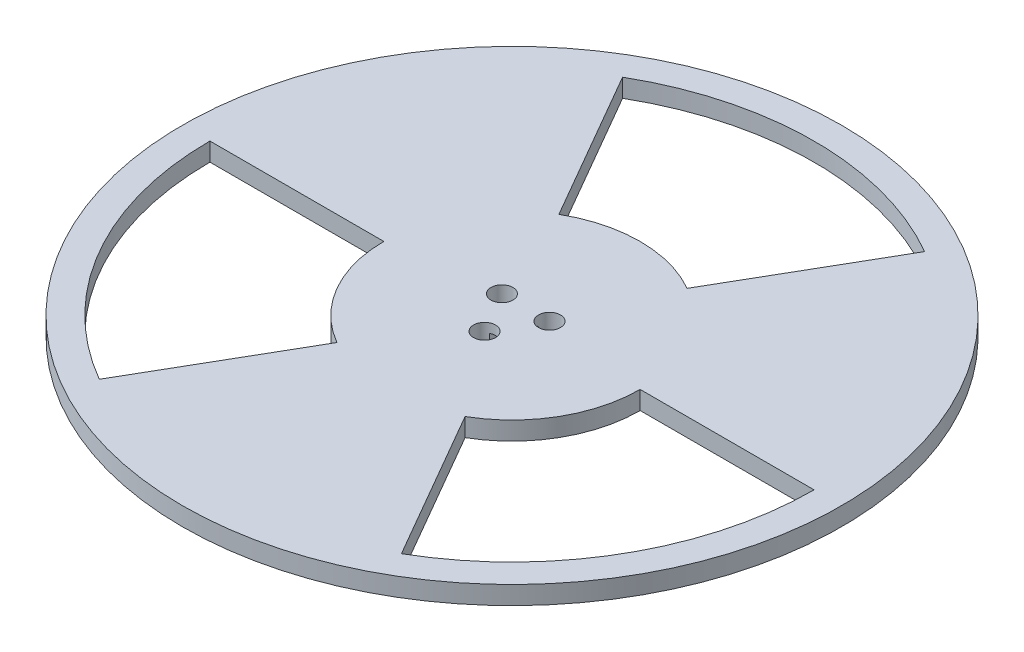
SolidWorks part; units mm, degrees
ref_plane "Front Plane" through (0, 0, 0) normal (0, 0, 1) x (1, 0, 0)
ref_plane "Top Plane" through (0, 0, 0) normal (0, 1, 0) x (1, 0, 0)
ref_plane "Right Plane" through (0, 0, 0) normal (1, 0, 0) x (0, 0, -1)
sketch "Sketch1" plane through (0, 0, 0) normal (0, 1, 0) x (1, 0, 0)
  circle A0 centre (0, 0) radius 18
  dimension "D1" = 36
extrude "Boss-Extrude1" add sketch "Sketch1" along normal blind 1
sketch "Sketch2" plane through (0, 0, 0) normal (0, -1, 0) x (1, 0, 0)
  circle A0 centre (0, 0) radius 2
  dimension "D1" = 4
extrude "Boss-Extrude2" add sketch "Sketch2" along normal blind 2
sketch "Sketch3" plane through (0, -2, 0) normal (0, -1, 0) x (1, 0, 0)
  circle A0 centre (0, 0) radius 1
  dimension "D1" = 2
extrude "Cut-Extrude1" cut sketch "Sketch3" against normal blind 2.5
fillet "Fillet1" radius 1 1 edges at (0, 0, 2)
sketch "Sketch4" plane through (0, 1, 0) normal (0, 1, 0) x (1, 0, 0)
  line L0 (-3.5, 6.0622) -> (-8.25, 14.2894)
  line L1 (3.5, 6.0622) -> (8.25, 14.2894)
  line L2 (0, 0) -> (0, 50000) construction
  line L3 (3.5, 6.0622) -> (0, 0) construction
  line L4 (0, 0) -> (-3.5, 6.0622) construction
  line L5 (7, 0) -> (16.5, 0)
  line L6 (3.5, -6.0622) -> (8.25, -14.2894)
  line L7 (-3.5, -6.0622) -> (-8.25, -14.2894)
  line L8 (-7, 0) -> (-16.5, 0)
  line L9 (0, 0) -> (43301.2702, 25000) construction
  arc A0 (-8.25, 14.2894) -> (8.25, 14.2894) centre (0, 0) cw
  circle A1 centre (0, 0) radius 18 construction
  arc A2 (-3.5, 6.0622) -> (3.5, 6.0622) centre (0, 0) cw
  arc A3 (16.5, 0) -> (8.25, -14.2894) centre (0, 0) cw
  arc A4 (7, 0) -> (3.5, -6.0622) centre (0, 0) cw
  arc A5 (-8.25, -14.2894) -> (-16.5, 0) centre (0, 0) cw
  arc A6 (-3.5, -6.0622) -> (-7, 0) centre (0, 0) cw
  circle A7 centre (1.299, 0.75) radius 0.6
  circle A8 centre (0, -1.5) radius 0.6
  circle A9 centre (-1.299, 0.75) radius 0.6
  point P22 (0, 0)
  point P23 (-3.0408, 1.2444)
  dimension "D4" = 7
  dimension "D7" = 1.2
  dimension "D1" = 30
  dimension "D2" = 30
  dimension "D3" = 1.5
  dimension "D6" = 30
  dimension "D8" = 1.5
  dimension "D10" = 1.5
  dimension "D5" = 3
  dimension "D9" = 3
extrude "Cut-Extrude2" cut sketch "Sketch4" along a picked direction on the side against the normal up to surface (1 mm away) contours L0 A0 L1 A2
equation "\"D2@Sketch4\"=\"D1@Sketch4\""
equation "\"D6@Sketch4\"=\"D1@Sketch4\""
equation "\"D10@Sketch4\"=\"D8@Sketch4\""
